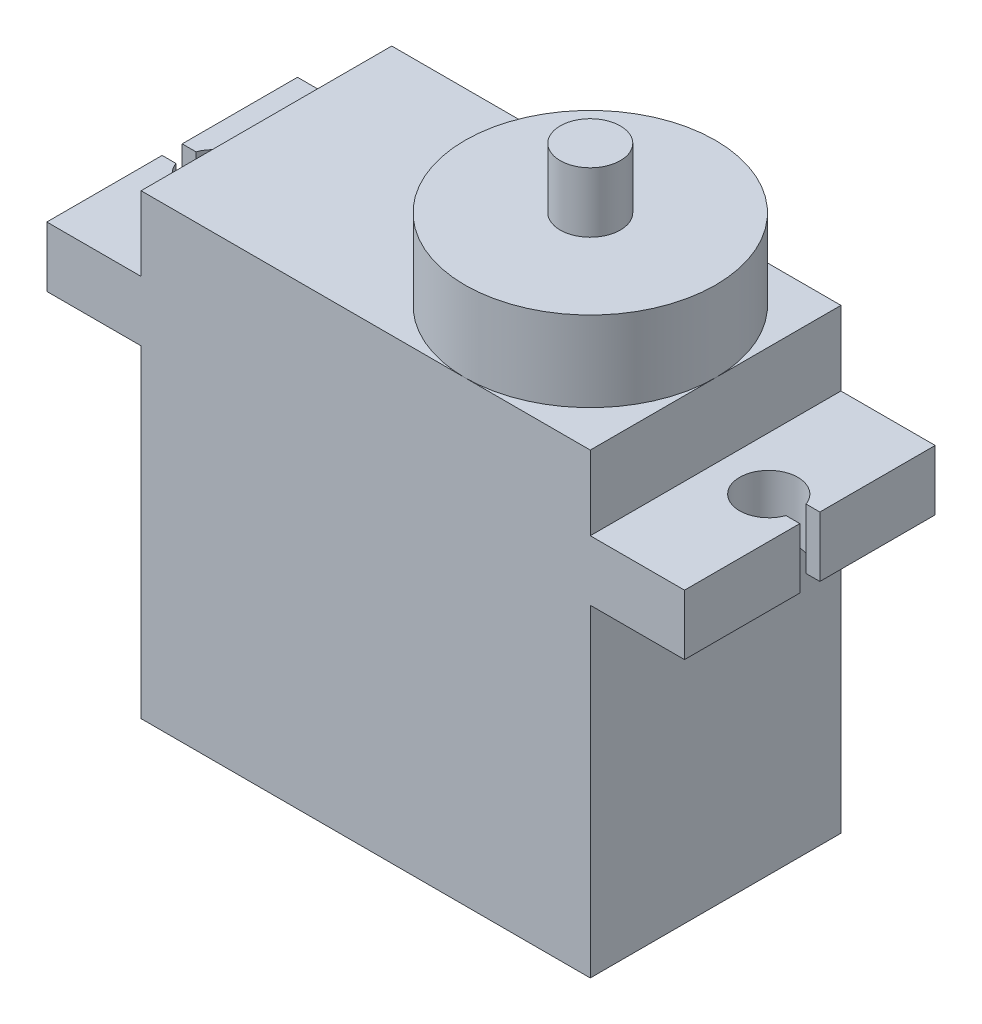
SolidWorks part; units mm, degrees
ref_plane "Front" through (0, 0, 0) normal (0, 0, 1) x (1, 0, 0)
ref_plane "Top" through (0, 0, 0) normal (0, 1, 0) x (1, 0, 0)
ref_plane "Right" through (0, 0, 0) normal (1, 0, 0) x (0, 0, -1)
sketch "草图1" plane through (0, 0, 0) normal (0, 0, 1) x (1, 0, 0)
  line L0 (0, 11.4) -> (0, -11.4) construction
  line L1 (-11.2, 11.4) -> (11.2, 11.4)
  line L2 (-11.2, 11.4) -> (-11.2, 7.7)
  line L3 (-11.2, -11.4) -> (11.2, -11.4)
  line L4 (11.2, 11.4) -> (11.2, 7.7)
  line L5 (-11.2, 11.4) -> (11.2, -11.4) construction
  line L6 (-11.2, -11.4) -> (11.2, 11.4) construction
  line L7 (11.2, 4.7) -> (15.9, 4.7)
  line L8 (-11.2, 4.7) -> (-15.9, 4.7)
  line L9 (11.2, 4.7) -> (11.2, -11.4)
  line L10 (-11.2, 7.7) -> (-15.9, 7.7)
  line L11 (-15.9, 4.7) -> (-15.9, 7.7)
  line L12 (15.9, 4.7) -> (15.9, 7.7)
  line L13 (11.2, 7.7) -> (15.9, 7.7)
  line L14 (-11.2, 4.7) -> (-11.2, -11.4)
  point P0 (0, 0)
  point P8 (-11.2, 4.7)
extrude "凸台-拉伸1" add sketch "草图1" along normal blind 12.5
sketch "草图5" plane through (0, 7.7, 0) normal (0, 1, 0) x (1, 0, 0)
  line L1 (-15.9, -12.5) -> (-15.9, 0) construction
  line L4 (-15.2111, -6.75) -> (-15.9, -6.75)
  line L6 (-15.2111, -5.75) -> (-15.9, -5.75)
  line L7 (-15.9, -6.75) -> (-15.9, -5.75)
  arc A0 (-15.2111, -6.75) -> (-15.2111, -5.75) centre (-13.85, -6.25) ccw
  dimension "D2" = 2.9
  dimension "D1" = 1
  dimension "D3" = 13.85
extrude "切除-拉伸2" cut sketch "草图5" against normal up to next
mirror "镜向2" about plane through (0, 0, 0) normal (1, 0, 0) of "切除-拉伸2"
sketch "草图6" plane through (0, 11.4, 0) normal (0, 1, 0) x (1, 0, 0)
  circle A0 centre (4.95, -6.25) radius 6.25
  dimension "D1" = 12.5
extrude "凸台-拉伸2" add sketch "草图6" along normal blind 4
sketch "草图7" plane through (0, 15.4, 0) normal (0, 1, 0) x (1, 0, 0)
  line L0 (4.95, 0) -> (4.95, -12.5) construction
  line L1 (4.95, 0) -> (-11.2, 0) construction
  circle A0 centre (4.95, -6.25) radius 6.25 construction
  circle A1 centre (4.95, -6.25) radius 1.5
extrude "凸台-拉伸3" add sketch "草图7" along normal blind 3
